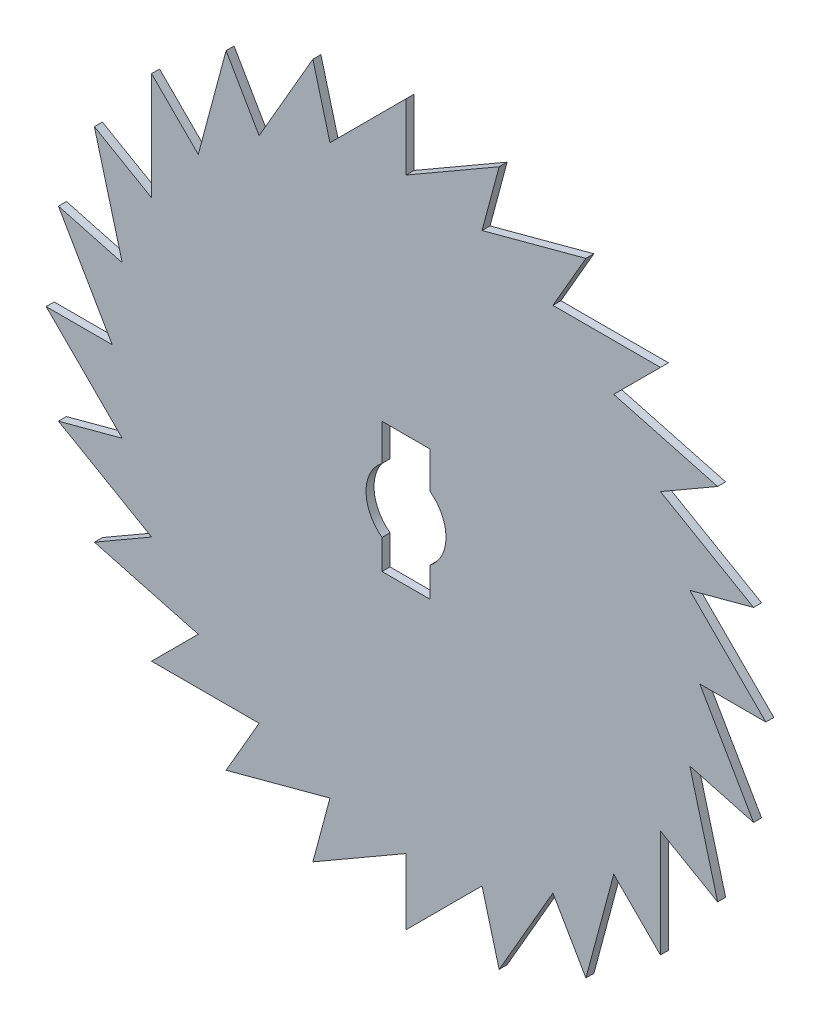
SolidWorks part; units mm, degrees
ref_plane "Front Plane" through (0, 0, 0) normal (0, 0, 1) x (1, 0, 0)
ref_plane "Top Plane" through (0, 0, 0) normal (0, 1, 0) x (1, 0, 0)
ref_plane "Right Plane" through (0, 0, 0) normal (1, 0, 0) x (0, 0, -1)
sketch "Sketch1" plane through (0, 0, 0) normal (0, 0, 1) x (1, 0, 0)
  line L0 (0, 0) -> (5.6741, 21.1759) construction
  line L1 (0, 0) -> (0, 73.4847) construction
  line L2 (0, 45) -> (0, 36.7423)
  line L3 (0, 36.7423) -> (11.6469, 43.4667)
  line L4 (9.5096, 35.4904) -> (22.5, 38.9711)
  line L5 (11.6469, 43.4667) -> (9.5096, 35.4904)
  line L6 (18.3712, 31.8198) -> (31.8198, 31.8198)
  line L7 (22.5, 38.9711) -> (18.3712, 31.8198)
  line L8 (25.9808, 25.9808) -> (38.9711, 22.5)
  line L9 (31.8198, 31.8198) -> (25.9808, 25.9808)
  line L10 (31.8198, 18.3712) -> (43.4667, 11.6469)
  line L11 (38.9711, 22.5) -> (31.8198, 18.3712)
  line L12 (35.4904, 9.5096) -> (45, 0)
  line L13 (43.4667, 11.6469) -> (35.4904, 9.5096)
  line L14 (36.7423, 0) -> (43.4667, -11.6469)
  line L15 (45, 0) -> (36.7423, 0)
  line L16 (35.4904, -9.5096) -> (38.9711, -22.5)
  line L17 (43.4667, -11.6469) -> (35.4904, -9.5096)
  line L18 (31.8198, -18.3712) -> (31.8198, -31.8198)
  line L19 (38.9711, -22.5) -> (31.8198, -18.3712)
  line L20 (25.9808, -25.9808) -> (22.5, -38.9711)
  line L21 (31.8198, -31.8198) -> (25.9808, -25.9808)
  line L22 (18.3712, -31.8198) -> (11.6469, -43.4667)
  line L23 (22.5, -38.9711) -> (18.3712, -31.8198)
  line L24 (9.5096, -35.4904) -> (0, -45)
  line L25 (11.6469, -43.4667) -> (9.5096, -35.4904)
  line L26 (0, -36.7423) -> (-11.6469, -43.4667)
  line L27 (0, -45) -> (0, -36.7423)
  line L28 (-9.5096, -35.4904) -> (-22.5, -38.9711)
  line L29 (-11.6469, -43.4667) -> (-9.5096, -35.4904)
  line L30 (-18.3712, -31.8198) -> (-31.8198, -31.8198)
  line L31 (-22.5, -38.9711) -> (-18.3712, -31.8198)
  line L32 (-25.9808, -25.9808) -> (-38.9711, -22.5)
  line L33 (-31.8198, -31.8198) -> (-25.9808, -25.9808)
  line L34 (-31.8198, -18.3712) -> (-43.4667, -11.6469)
  line L35 (-38.9711, -22.5) -> (-31.8198, -18.3712)
  line L36 (-35.4904, -9.5096) -> (-45, 0)
  line L37 (-43.4667, -11.6469) -> (-35.4904, -9.5096)
  line L38 (-36.7423, 0) -> (-43.4667, 11.6469)
  line L39 (-45, 0) -> (-36.7423, 0)
  line L40 (-35.4904, 9.5096) -> (-38.9711, 22.5)
  line L41 (-43.4667, 11.6469) -> (-35.4904, 9.5096)
  line L42 (-31.8198, 18.3712) -> (-31.8198, 31.8198)
  line L43 (-38.9711, 22.5) -> (-31.8198, 18.3712)
  line L44 (-25.9808, 25.9808) -> (-22.5, 38.9711)
  line L45 (-31.8198, 31.8198) -> (-25.9808, 25.9808)
  line L46 (-18.3712, 31.8198) -> (-11.6469, 43.4667)
  line L47 (-22.5, 38.9711) -> (-18.3712, 31.8198)
  line L48 (-9.5096, 35.4904) -> (0, 45)
  line L49 (-11.6469, 43.4667) -> (-9.5096, 35.4904)
  circle A0 centre (0, 0) radius 45 construction
  circle A1 centre (0, 0) radius 5
  point P80 (0, 0)
  dimension "D1" = 90
  dimension "D5" = 10
  dimension "D2" = 15
  dimension "D3" = 60
  dimension "D4" = 24
extrude "Boss-Extrude1" add sketch "Sketch1" along normal blind 1
sketch "Sketch2" plane through (0, 0, 0) normal (1, 0, 0) x (0, 0, -1)
sketch "Sketch3" plane through (0, 0, 1) normal (0, 0, 1) x (1, 0, 0)
  line L1 (-3, 8.5738) -> (3, 8.5738)
  line L2 (-3, 8.5738) -> (-3, -7.6956)
  line L3 (-3, -7.6956) -> (3, -7.6956)
  line L4 (3, 8.5738) -> (3, -7.6956)
  circle A0 centre (0, 0) radius 5 construction
  dimension "D1" = 3
  dimension "D2" = 3
extrude "Cut-Extrude1" cut sketch "Sketch3" against normal blind 10
